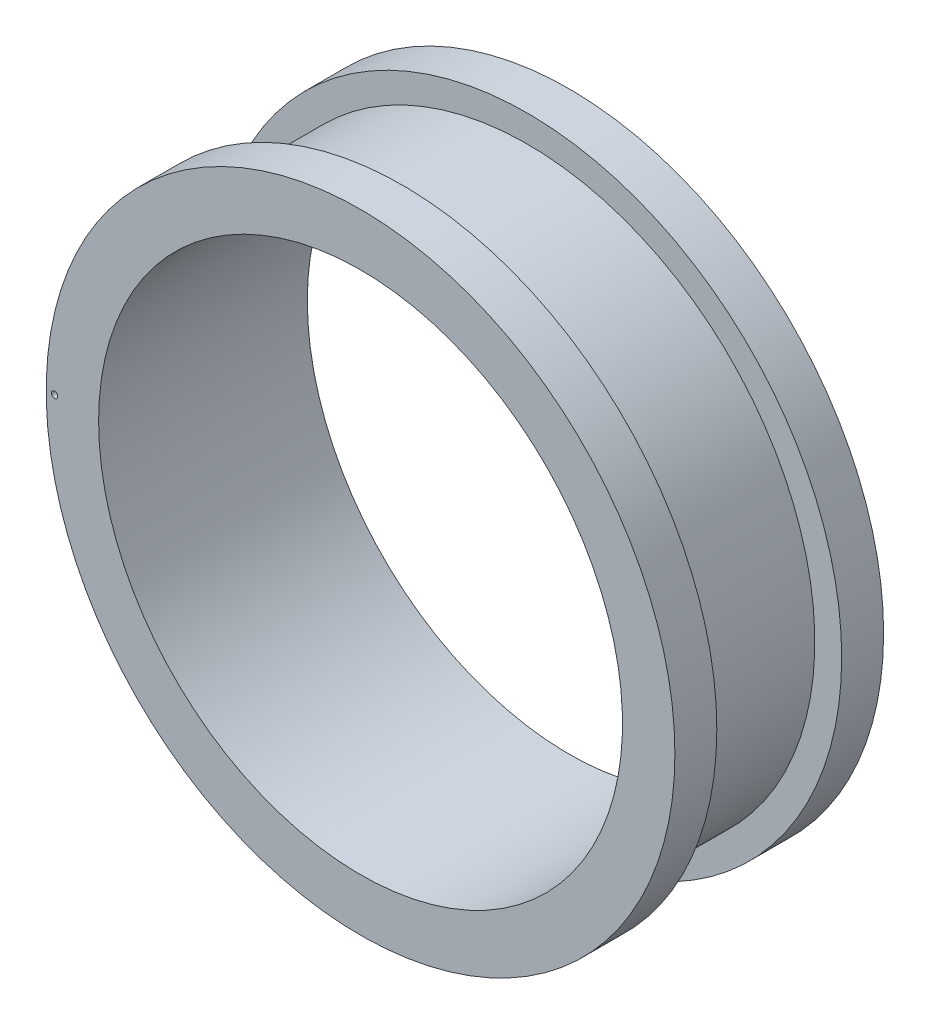
SolidWorks part; units mm, degrees
ref_plane "Front Plane" through (0, 0, 0) normal (0, 0, 1) x (1, 0, 0)
ref_plane "Top Plane" through (0, 0, 0) normal (0, 1, 0) x (1, 0, 0)
ref_plane "Right Plane" through (0, 0, 0) normal (1, 0, 0) x (0, 0, -1)
sketch "Sketch1" plane through (0, 0, 0) normal (0, 0, 1) x (1, 0, 0)
  circle A0 centre (0, 0) radius 150
  dimension "D1" = 300
extrude "Boss-Extrude2" add sketch "Sketch1" against normal blind 20
sketch "Sketch2" plane through (0, 0, -20) normal (0, 0, -1) x (-1, 0, 0)
  circle A0 centre (0, 0) radius 125
  dimension "D1" = 250
extrude "Cut-Extrude1" cut sketch "Sketch2" against normal up to next
sketch "Sketch3" plane through (0, 0, 0) normal (0, 0, 1) x (1, 0, 0)
  circle A0 centre (0, 0) radius 137.1715
extrude "Boss-Extrude3" add sketch "Sketch3" along normal blind 59.5889
sketch "Sketch4" plane through (0, 0, 59.5889) normal (0, 0, 1) x (1, 0, 0)
  circle A0 centre (0, 0) radius 150
extrude "Boss-Extrude4" add sketch "Sketch4" along normal blind 20
sketch "Sketch6" plane through (0, 0, 0) normal (0, 0, -1) x (-1, 0, 0)
  circle A0 centre (0, 0) radius 125
extrude "Cut-Extrude2" cut sketch "Sketch6" against normal through all
sketch "Sketch7" plane through (0, 0, 79.5889) normal (0, 0, 1) x (1, 0, 0)
  circle A0 centre (-145.9902, 0.3813) radius 1.5
extrude "Cut-Extrude5" cut sketch "Sketch7" against normal up to next
